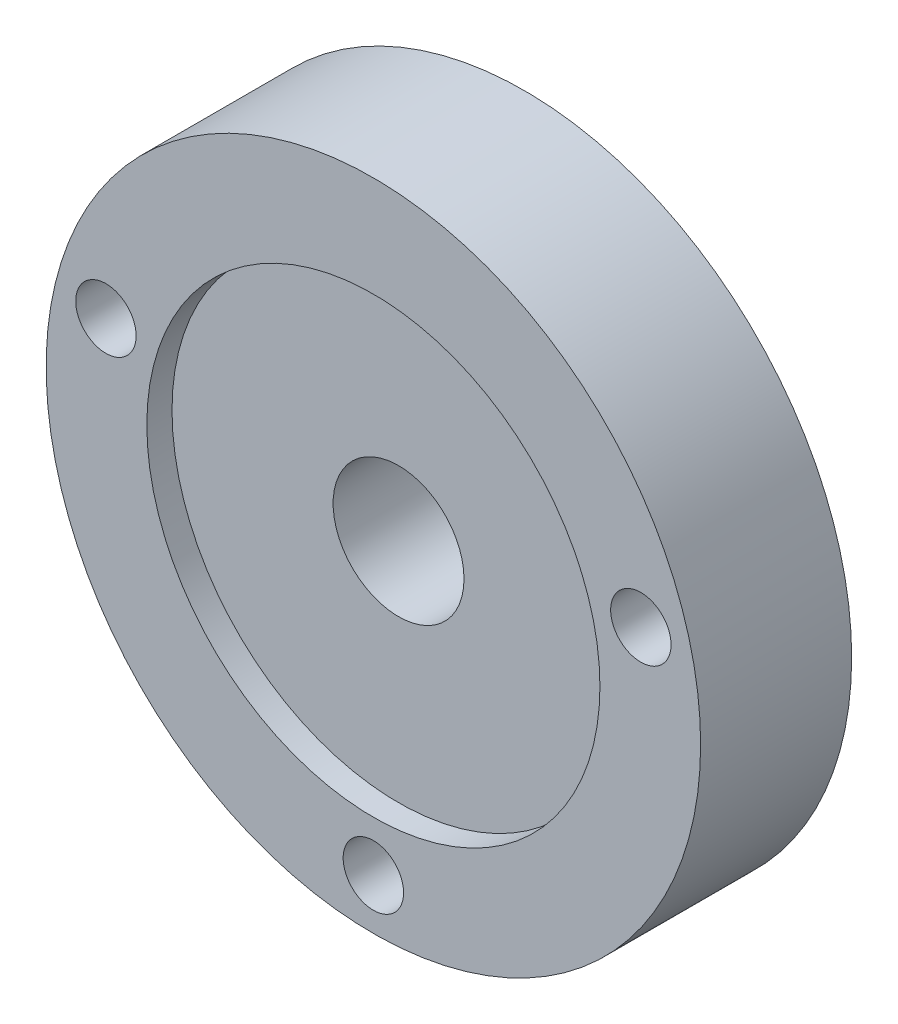
SolidWorks part; units mm, degrees
ref_plane "Plan de face" through (0, 0, 0) normal (0, 0, 1) x (1, 0, 0)
ref_plane "Plan de dessus" through (0, 0, 0) normal (0, 1, 0) x (1, 0, 0)
ref_plane "Plan de droite" through (0, 0, 0) normal (1, 0, 0) x (0, 0, -1)
sketch "Esquisse1" plane through (0, 0, 0) normal (0, 0, 1) x (1, 0, 0)
  circle A0 centre (0, 0) radius 32.5
  dimension "D1" = 65
extrude "Boss.-Extru.1" add sketch "Esquisse1" along normal blind 15
sketch "Esquisse2" plane through (0, 0, 15) normal (0, 0, 1) x (1, 0, 0)
  circle A0 centre (0, 0) radius 22.5
  dimension "D1" = 45
extrude "Enlèv. mat.-Extru.1" cut sketch "Esquisse2" against normal blind 2.5
sketch "Esquisse3" plane through (0, 0, 12.5) normal (0, 0, 1) x (1, 0, 0)
  circle A0 centre (0, 0) radius 6.5
  dimension "D1" = 13
extrude "Enlèv. mat.-Extru.2" cut sketch "Esquisse3" against normal through all
hole_wizard "Trous de centrage Ø6.0mm1" positions "Esquisse5" profile "Esquisse4" hole size "Ø6.0" standard "ISO" end condition through all
sketch "Esquisse5" plane through (0, 0, 15) normal (0, 0, 1) x (1, 0, 0)
  point P0 (0, -27.5)
  point P2 (-26.563, 7.1175)
  point P4 (26.563, 7.1175)
sketch "Esquisse4" plane through (0, -27.5, 15) normal (1, 0, 0) x (0, -1, 0)
  line L0 (0, 0) -> (0, 15)
  line L1 (0, 15) -> (3, 15)
  line L2 (3, 15) -> (3, 0)
  line L5 (3, 0) -> (0, 0)
  line L11 (0, -6.35) -> (0, 107.95) construction
  dimension "Diamètre du perçage jusqu'au prochain" = 6
  dimension "Profondeur du perçage jusqu'au prochain" = 15
